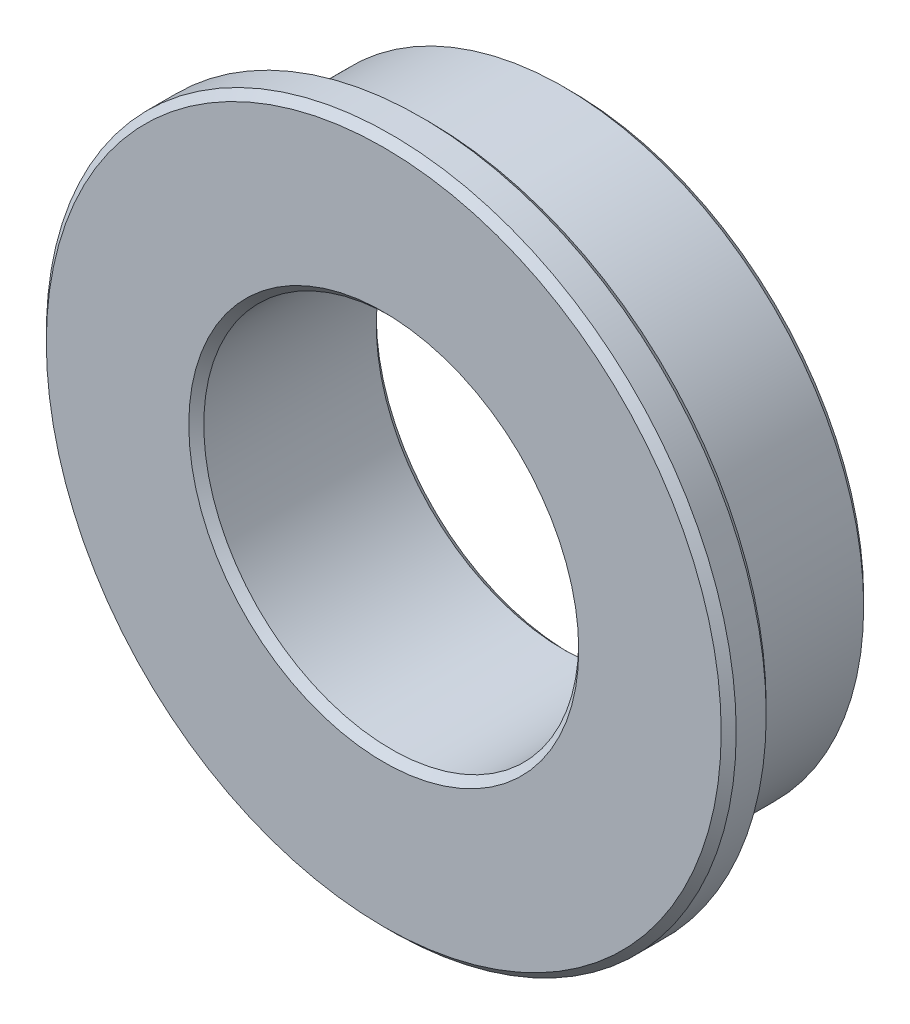
SolidWorks part; units mm, degrees
other "Bearing_8-5-2.5"
material "1.5714 (16NiCr4)"
ref_plane "Front" through (0, 0, 0) normal (0, 0, 1) x (1, 0, 0)
ref_plane "Top" through (0, 0, 0) normal (0, 1, 0) x (1, 0, 0)
ref_plane "Right" through (0, 0, 0) normal (1, 0, 0) x (0, 0, -1)
sketch "BearingSke" plane through (0, 0, 0) normal (0, 0, 1) x (1, 0, 0)
  circle A0 centre (0, 0) radius 4
  circle A1 centre (0, 0) radius 2.5
  dimension "D1" = 8
  dimension "D2" = 5
extrude "Bearing" add sketch "BearingSke" along normal blind 2.5
sketch "FlangeSke" plane through (0, 0, 2.5) normal (0, 0, 1) x (1, 0, 0)
  circle A0 centre (0, 0) radius 4.6
  circle A1 centre (0, 0) radius 4
  circle A2 centre (0, 0) radius 4 construction
  dimension "D1" = 9.2
extrude "Flange" add sketch "FlangeSke" against normal blind 0.6
chamfer "Chamfer" distance 0.1 angle 45 5 edges at (2.5, 0, 0) (2.5, 0, 2.5) (4.6, 0, 1.9) (4.6, 0, 2.5) (4, 0, 0)
